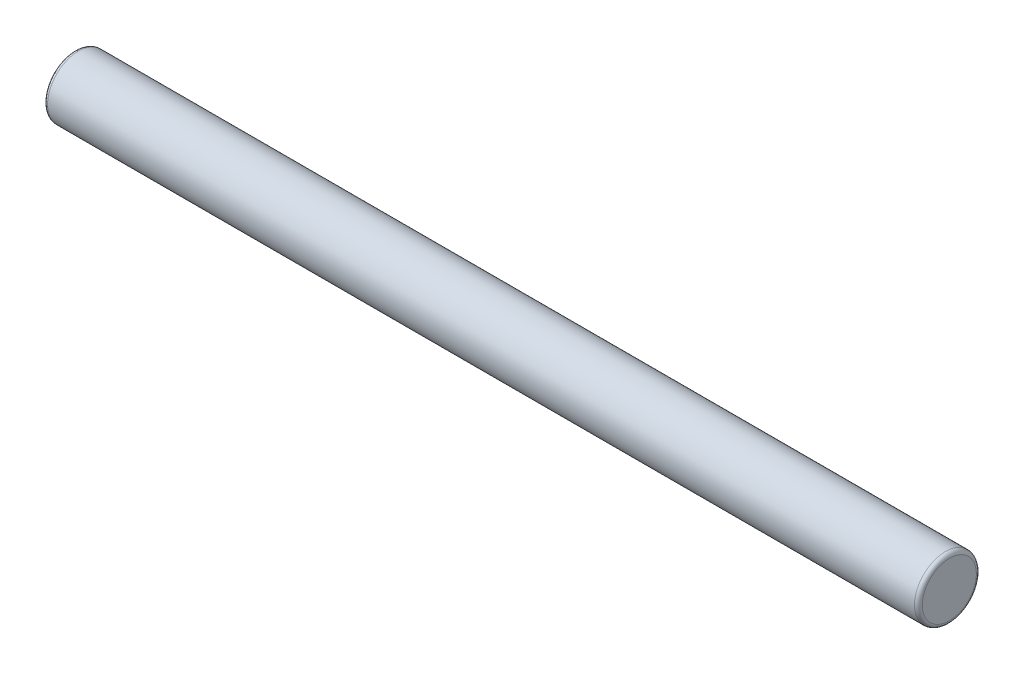
SolidWorks part; units mm, degrees
material "AISI 1020"
ref_plane "Front Plane" through (0, 0, 0) normal (0, 0, 1) x (1, 0, 0)
ref_plane "Top Plane" through (0, 0, 0) normal (0, 1, 0) x (1, 0, 0)
ref_plane "Right Plane" through (0, 0, 0) normal (1, 0, 0) x (0, 0, -1)
sketch "Sketch1" plane through (0, 0, 0) normal (1, 0, 0) x (0, 0, -1)
  circle A0 centre (0, 0) radius 4
  dimension "D1" = 8
extrude "Boss-Extrude1" add sketch "Sketch1" along normal blind 113
fillet "Fillet1" radius 0.508 2 edges at (113, 0, -4) (0, 0, -4)
